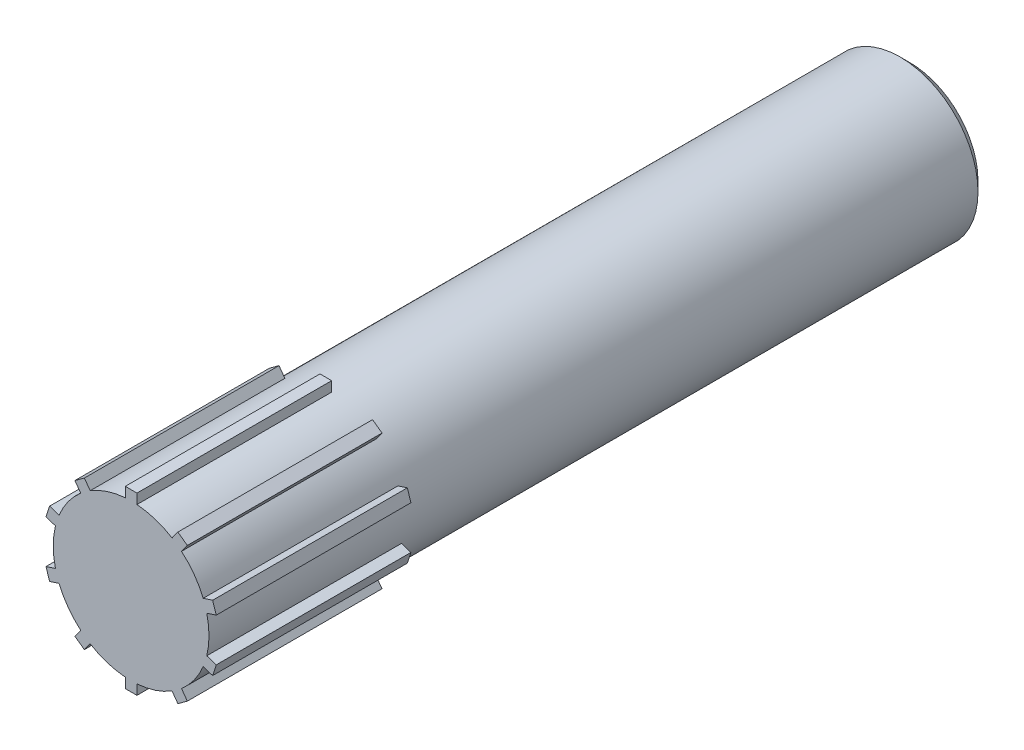
SolidWorks part; units mm, degrees
ref_plane "Front Plane" through (0, 0, 0) normal (0, 0, 1) x (1, 0, 0)
ref_plane "Top Plane" through (0, 0, 0) normal (0, 1, 0) x (1, 0, 0)
ref_plane "Right Plane" through (0, 0, 0) normal (1, 0, 0) x (0, 0, -1)
sketch "Sketch1" plane through (0, 0, 0) normal (0, 0, 1) x (1, 0, 0)
  circle A0 centre (0, 0) radius 4
  dimension "D1" = 8
extrude "Boss-Extrude1" add sketch "Sketch1" along normal blind 40
sketch "Sketch2" plane through (0, 0, 0) normal (0, 1, 0) x (1, 0, 0)
  line L0 (0, 0) -> (0, -40) construction
  line L1 (4, 0) -> (-4, 0) construction
  line L2 (-4, -40) -> (4, -40) construction
  line L3 (0, -5) -> (0, -9) construction
  line L4 (1.5, -5) -> (1.5, -9)
  line L5 (-1.5, -5) -> (-1.5, -9)
  arc A0 (1.5, -5) -> (-1.5, -5) centre (0, -5) ccw
  arc A1 (-1.5, -9) -> (1.5, -9) centre (0, -9) ccw
  point P8 (0, -7)
  dimension "D1" = 1.5
  dimension "D2" = 4
  dimension "D3" = 5
extrude "Cut-Extrude1" cut sketch "Sketch2" against normal through all from offset 2.5 offset against normal yes
sketch "Sketch3" plane through (0, 0, 40) normal (0, 0, 1) x (1, 0, 0)
  line L0 (0, 0) -> (0, 5.8627) construction
  line L2 (-0.3, 4.5) -> (0.3, 4.5)
  line L3 (-0.3, 4.5) -> (-0.3, 2.6033)
  line L4 (-0.3, 2.6033) -> (0.3, 2.6033)
  line L5 (0.3, 4.5) -> (0.3, 2.6033)
  dimension "D1" = 0.6
  dimension "D2" = 4.5
extrude "Boss-Extrude2" add sketch "Sketch3" against normal blind 10
pattern_circular "CirPattern1" count 10 over 360 about axis through (0, 0, 0) along (0, 0, 1) of "Boss-Extrude2"
chamfer "Chamfer1" distance 0.5 angle 45 1 edges at (4, 0, 0)
